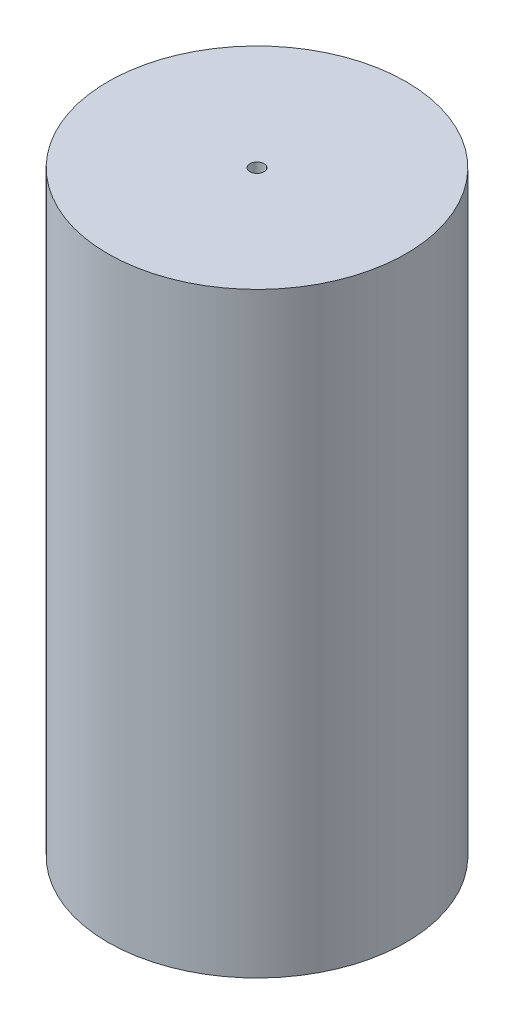
SolidWorks part; units mm, degrees
ref_plane "Ebene vorne" through (0, 0, 0) normal (0, 0, 1) x (1, 0, 0)
ref_plane "Ebene oben" through (0, 0, 0) normal (0, 1, 0) x (1, 0, 0)
ref_plane "Ebene rechts" through (0, 0, 0) normal (1, 0, 0) x (0, 0, -1)
sketch "Skizze1" plane through (0, 0, 0) normal (0, 1, 0) x (1, 0, 0)
  circle A0 centre (0, 0) radius 35
  dimension "D1" = 70
extrude "Aufsatz-Linear austragen2" add sketch "Skizze1" along normal blind 140 contours A0
sketch "Außengewinde" plane through (0, 0, 0) normal (0, -1, 0) x (1, 0, 0)
  circle A0 centre (0, 0) radius 3
  dimension "D1" = 6
extrude "Aufsatz-Linear austragen4" add sketch "Außengewinde" along normal blind 10
cosmetic thread "Gewindedarstellung5" parameters "D2"=4.891
sketch "Innengewinde" plane through (0, 140, 0) normal (0, 1, 0) x (1, 0, 0)
  circle A0 centre (0, 0) radius 8.1138
hole_wizard "Kernloch für M4x0.71" positions "Skizze6" profile "Skizze7" hole size "M4x0.7" standard "ANSI Metrisch"
sketch "Skizze6" plane through (0, 140, 0) normal (0, 1, 0) x (1, 0, 0)
  point P0 (0, 0)
sketch "Skizze7" plane through (0, 140, 0) normal (1, 0, 0) x (0, 0, 1)
  line L0 (0, 0) -> (0, 15.9914)
  line L1 (0, 15.9914) -> (1.65, 15)
  line L2 (1.65, 15) -> (1.65, 0)
  line L5 (1.65, 0) -> (0, 0)
  line L10 (0, 15.9914) -> (-1.65, 15) construction
  line L11 (0, -6.35) -> (0, 107.95) construction
  dimension "Bohrerdurchmesser" = 3.3
  dimension "Bohrungstiefe" = 15
  dimension "Spitzenwinkel" = 118
